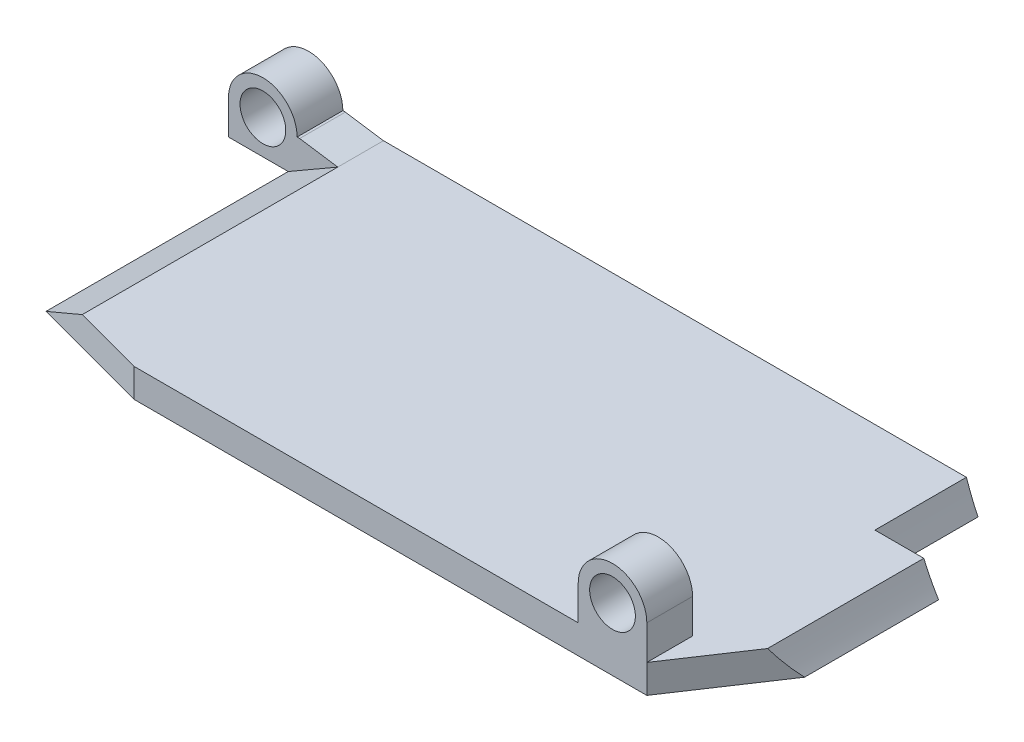
SolidWorks part; units mm, degrees
material "1060-H16"
ref_plane "前视基准面" through (0, 0, 0) normal (0, 0, 1) x (1, 0, 0)
ref_plane "上视基准面" through (0, 0, 0) normal (0, 1, 0) x (1, 0, 0)
ref_plane "右视基准面" through (0, 0, 0) normal (1, 0, 0) x (0, 0, -1)
sketch "草图2" plane through (0, 0, -2) normal (0, 0, -1) x (-1, 0, 0)
  line L0 (15.5849, 24.75) -> (-14.8556, 24.75)
  line L1 (15.5849, 24.75) -> (13.4199, 26)
  line L2 (13.4199, 26) -> (-14.2084, 26)
  arc A2 (-14.8556, 24.75) -> (-14.8556, 34.25) centre (-22.5, 29.5) ccw
  arc A3 (-14.8556, 34.25) -> (-14.8556, 24.75) centre (-22.5, 29.5) ccw
  arc A4 (-14.8556, 24.75) -> (-14.8556, 34.25) centre (-22.5, 29.5) ccw
  arc A5 (-14.8556, 34.25) -> (-14.8556, 24.75) centre (-22.5, 29.5) ccw
  dimension "D1" = 1.25
  dimension "D2" = 30
  dimension "D4" = 30.4405
  dimension "D3" = 0
extrude "凸台-拉伸1" add sketch "草图2" along normal blind 14
sketch "草图3" plane through (0, 0, -16) normal (0, 0, -1) x (-1, 0, 0)
  line L0 (-12.5784, 24.75) -> (-17.3583, 24.75)
  line L1 (-17.3583, 24.75) -> (-16.0628, 32.25)
  line L2 (-16.0628, 32.25) -> (-11.8493, 32.25)
  arc A0 (-12.5784, 24.75) -> (-11.8493, 32.25) centre (-22.5, 29.5) ccw construction
  arc A1 (-12.5784, 24.75) -> (-11.8493, 32.25) centre (-22.5, 29.5) ccw
extrude "切除-拉伸1" cut sketch "草图3" against normal blind 4
sketch "草图4" plane through (0, 24.75, 0) normal (0, -1, 0) x (1, 0, 0)
  line L0 (12.0963, -2) -> (15.4296, -7)
  line L1 (14.8556, -6.1389) -> (12.0963, -2) construction
  line L3 (-15.5849, -2) -> (14.8556, -2) construction
  line L4 (15.4296, -7) -> (15.4296, -2)
  line L7 (-10.3293, -2) -> (-15.5849, -3.4082)
  line L8 (-15.5849, -3.4082) -> (-10.3293, -2) construction
  line L9 (-15.5849, -16) -> (-15.5849, -2) construction
  line L10 (-15.5849, -3.4082) -> (-15.5849, -2)
  line L11 (-15.5849, -2) -> (-10.3293, -2)
  line L12 (15.4296, -2) -> (12.0963, -2)
extrude "切除-拉伸2" cut sketch "草图4" against normal through all
sketch "草图6" plane through (0, 0, -16) normal (0, 0, -1) x (-1, 0, 0)
  line L0 (15.5849, 24.75) -> (18.1957, 24.75)
  line L1 (18.1957, 24.75) -> (18.1957, 26.25)
  line L2 (18.1957, 26.25) -> (15.0857, 26.25)
  line L3 (15.0857, 26.25) -> (13.4199, 26)
  circle A0 centre (16.6957, 26.25) radius 1.5
  line M5 (15.5849, 24.75) -> (13.4199, 26)
  dimension "D3" = 3
  dimension "D4" = 2.6108
  dimension "D1" = 1.5
  dimension "D2" = 3.11
extrude "凸台-拉伸2" add sketch "草图6" against normal blind 2 contours A0 L2 L3 L0 M5 | L2 A0 | A0 L0 L1 | L2 A0
sketch "草图7" plane through (0, 0, -2) normal (0, 0, 1) x (1, 0, 0)
  line L0 (12.0963, 26) -> (12.0963, 27.5)
  line L1 (12.0963, 32.25) -> (12.0963, 24.75) construction
  line L2 (12.0963, 27.5) -> (9.0963, 27.5)
  line L3 (9.0963, 27.5) -> (9.0963, 26)
  line L4 (-10.3293, 26) -> (12.0963, 26) construction
  line L5 (9.0963, 26) -> (12.0963, 26)
  circle A0 centre (10.5963, 27.5) radius 1.5
  line M3 (12.0963, 26) -> (-10.3293, 26)
  dimension "D1" = 3
  dimension "D2" = 1.5
extrude "凸台-拉伸3" add sketch "草图7" against normal blind 2 contours A0 L0 M3 | A0 L3 L5 | L2 A0 | L2 A0
hole_wizard "大小mm 暗销孔1" positions "草图8" profile "草图9" hole size "Ø2.0" standard "GB" end condition through all
sketch "草图8" plane through (0, 0, -16) normal (0, 0, -1) x (-1, 0, 0)
  line L0 (18.1957, 24.75) -> (-12.5784, 24.75) construction
  line L2 (18.1957, 24.75) -> (18.1957, 26.25) construction
  point P0 (16.6918, 26.25)
  dimension "D1" = 1.5
  dimension "D2" = 1.504
sketch "草图9" plane through (-16.6918, 26.25, -16) normal (1, 0, 0) x (0, 1, 0)
  line L0 (0, 0) -> (0, 14)
  line L1 (0, 14) -> (1, 14)
  line L2 (1, 14) -> (1, 0)
  line L5 (1, 0) -> (0, 0)
  line L11 (0, -6.35) -> (0, 107.95) construction
  dimension "通孔孔直径" = 2
  dimension "通孔孔深度" = 14
hole_wizard "大小mm 暗销孔2" positions "草图10" profile "草图11" hole size "Ø2.0" standard "GB" end condition through all
sketch "草图10" plane through (0, 0, -2) normal (0, 0, 1) x (1, 0, 0)
  line L0 (9.0963, 27.5) -> (9.0963, 26) construction
  line L3 (-10.3293, 26) -> (9.0963, 26) construction
  point P0 (10.5963, 27.5)
  dimension "D1" = 1.5
  dimension "D2" = 1.5
sketch "草图11" plane through (10.5963, 27.5, -2) normal (1, 0, 0) x (0, -1, 0)
  line L0 (0, 0) -> (0, 14)
  line L1 (0, 14) -> (1, 14)
  line L2 (1, 14) -> (1, 0)
  line L5 (1, 0) -> (0, 0)
  line L11 (0, -6.35) -> (0, 107.95) construction
  dimension "通孔孔直径" = 2
  dimension "通孔孔深度" = 14
